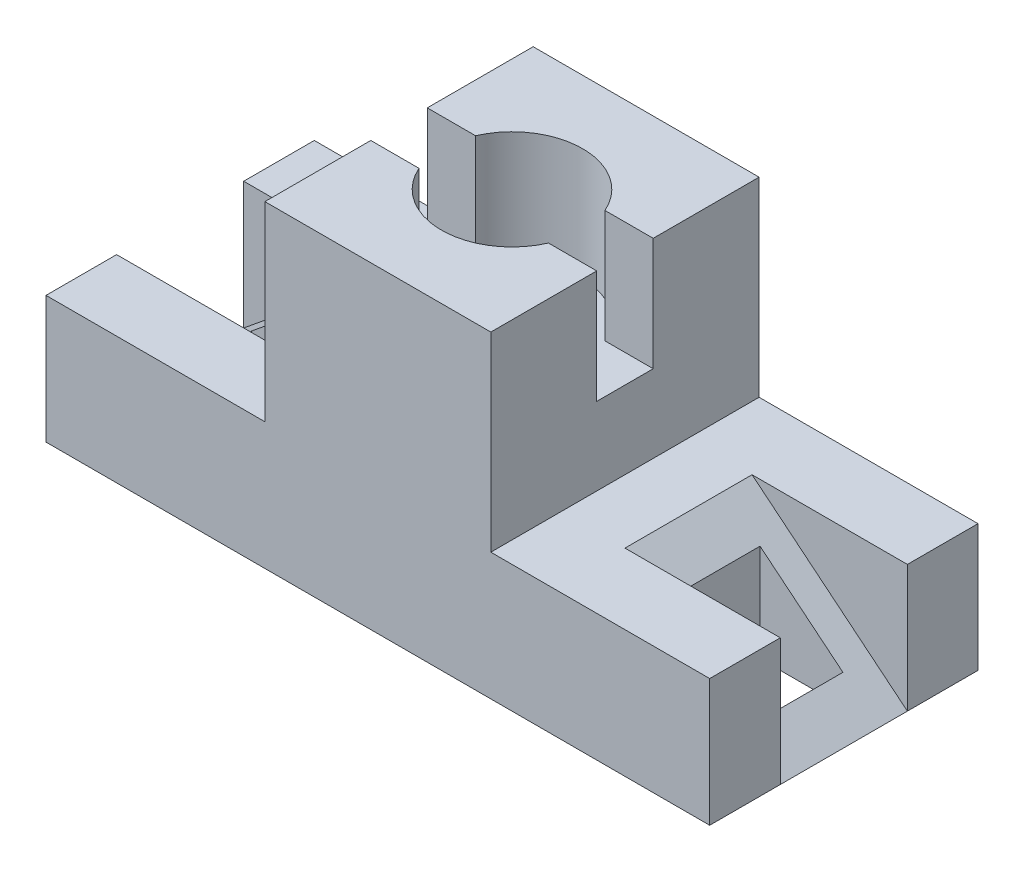
SolidWorks part; units mm, degrees
ref_plane "Front Plane" through (0, 0, 0) normal (0, 0, 1) x (1, 0, 0)
ref_plane "Top Plane" through (0, 0, 0) normal (0, 1, 0) x (1, 0, 0)
ref_plane "Right Plane" through (0, 0, 0) normal (1, 0, 0) x (0, 0, -1)
sketch "Sketch1" plane through (0, 0, 0) normal (0, 0, 1) x (1, 0, 0)
  line L0 (0, 0) -> (0, 18)
  line L1 (0, 18) -> (31, 18)
  line L2 (31, 18) -> (31, 45)
  line L3 (31, 45) -> (63, 45)
  line L4 (63, 45) -> (63, 18)
  line L5 (63, 18) -> (94, 18)
  line L6 (94, 18) -> (94, 0)
  line L7 (94, 0) -> (0, 0)
  dimension "D1" = 31
  dimension "D2" = 63
  dimension "D3" = 18
  dimension "D4" = 45
extrude "Boss-Extrude1" add sketch "Sketch1" along normal blind 38
sketch "Sketch2" plane through (0, 45, 0) normal (0, 1, 0) x (1, 0, 0)
  line L0 (63, -15) -> (56.1652, -15)
  line L2 (31, -38) -> (31, 0) construction
  line L5 (63, -23) -> (56.1652, -23)
  line L6 (37.8348, -23) -> (31, -23)
  line L7 (63, 0) -> (31, 0) construction
  line L10 (37.8348, -15) -> (31, -15)
  arc A0 (56.1652, -15) -> (37.8348, -15) centre (47, -19) ccw
  arc A1 (37.8348, -23) -> (56.1652, -23) centre (47, -19) ccw
  line M3 (31, 0) -> (31, -38)
  line M5 (63, -38) -> (63, 0)
  dimension "D1" = 10
  dimension "D2" = 6.8348
  dimension "D3" = 16
  dimension "D4" = 15
  dimension "D5" = 32
extrude "Cut-Extrude1" cut sketch "Sketch2" against normal blind 16 contours L6 A1 L5 L0 A0 L10 M5 M3
sketch "Sketch3" plane through (0, 18, 0) normal (0, 1, 0) x (1, 0, 0)
  line L1 (31, 0) -> (0, 0) construction
  line L2 (22, 0) -> (22, -38)
  line L3 (31, -38) -> (0, -38) construction
ref_plane "Plane1" through (0, 0, 0) normal (0.6332, -0.774, 0) x (-0.774, -0.6332, 0)
sketch "Sketch4" plane through (0, 0, 0) normal (0.6332, -0.774, 0) x (-0.774, -0.6332, 0)
  line L2 (0, -10) -> (0, -28)
  line L3 (0, -28) -> (-28.4253, -28)
  line L5 (0, -10) -> (-28.4253, -10)
  line L6 (-28.4253, -28) -> (-28.4253, -10)
  dimension "D1" = 28.4253
  dimension "D2" = 10
  dimension "D3" = 28
extrude "Cut-Extrude2" cut sketch "Sketch4" against normal blind 46
sketch "Sketch5" plane through (0, 18, 0) normal (0, 1, 0) x (1, 0, 0)
  line L0 (22, -10) -> (22, -28) construction
  line L2 (22, -28) -> (0, -28) construction
  line L4 (5.13, -14) -> (5.13, -24)
  line L5 (5.13, -24) -> (16.87, -24)
  line L7 (5.13, -14) -> (16.87, -14)
  line L8 (16.87, -24) -> (16.87, -14)
  dimension "D1" = 5.13
  dimension "D2" = 16.87
  dimension "D3" = 4
  dimension "D4" = 14
extrude "Cut-Extrude3" cut sketch "Sketch5" against normal blind 76
ref_plane "Plane2" through (47, 0, 0) normal (1, 0, 0) x (0, 0, -1)
mirror "Mirror1" about plane through (47, 0, 0) normal (1, 0, 0) of "Cut-Extrude2", "Cut-Extrude3"
